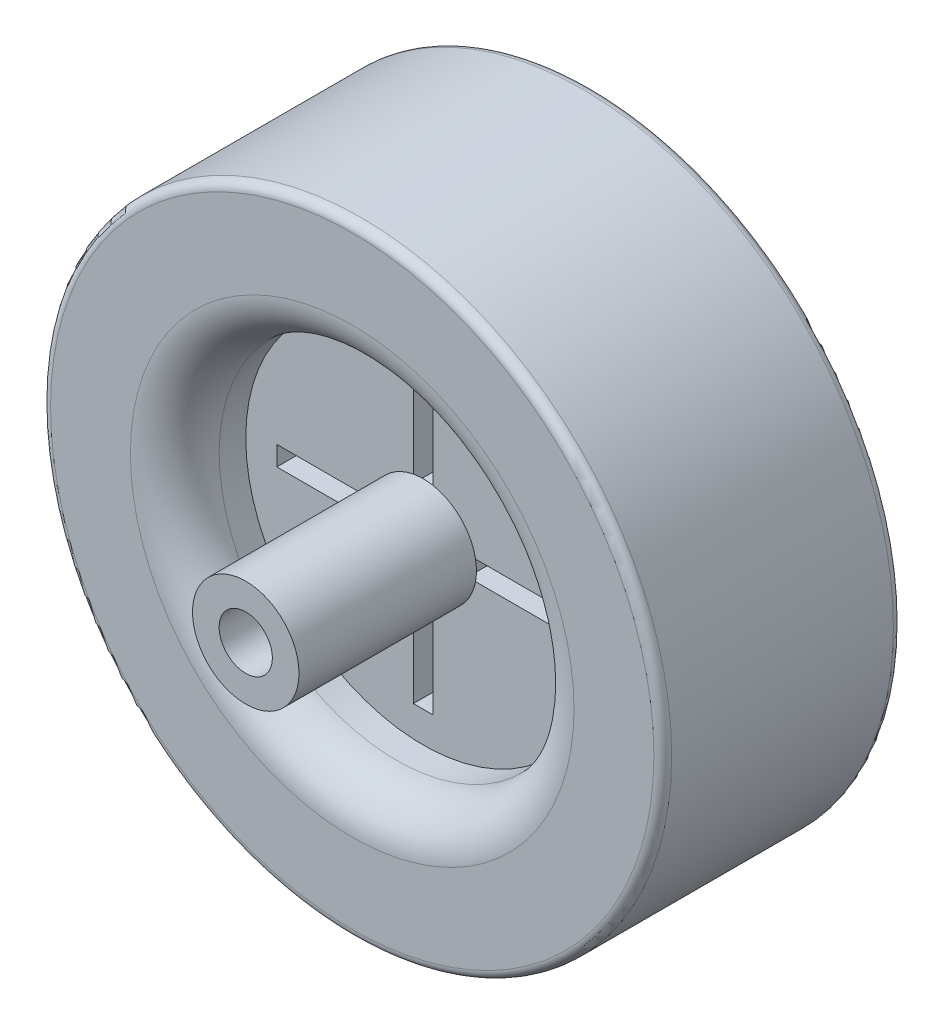
SolidWorks part; units mm, degrees
ref_plane "前视基准面" through (0, 0, 0) normal (0, 0, 1) x (1, 0, 0)
ref_plane "上视基准面" through (0, 0, 0) normal (0, 1, 0) x (1, 0, 0)
ref_plane "右视基准面" through (0, 0, 0) normal (1, 0, 0) x (0, 0, -1)
sketch "草图1" plane through (0, 0, 0) normal (0, 0, 1) x (1, 0, 0)
  circle A0 centre (0, 0) radius 35
extrude "凸台-拉伸1" add sketch "草图1" along normal blind 27
sketch "草图2" plane through (0, 0, 0) normal (0, 0, -1) x (-1, 0, 0)
  circle A0 centre (0, 0) radius 20
extrude "切除-拉伸1" cut sketch "草图2" against normal blind 8
sketch "草图3" plane through (0, 0, 27) normal (0, 0, 1) x (1, 0, 0)
  circle A0 centre (0, 0) radius 20
extrude "切除-拉伸2" cut sketch "草图3" against normal blind 8
fillet "圆角3" radius 5 1 edges at (-20, 0, 0)
fillet "圆角4" radius 5 1 edges at (20, 0, 27)
sketch "草图4" plane through (0, 0, 19) normal (0, 0, 1) x (1, 0, 0)
  circle A0 centre (0, 0) radius 6
extrude "凸台-拉伸2" add sketch "草图4" along normal blind 20
sketch "草图5" plane through (0, 0, 39) normal (0, 0, 1) x (1, 0, 0)
  circle A0 centre (0, 0) radius 3
extrude "切除-拉伸3" cut sketch "草图5" against normal blind 6
fillet "圆角5" radius 1 1 edges at (35, 0, 0)
fillet "圆角6" radius 1 1 edges at (35, 0, 27)
sketch "草图6" plane through (0, 0, 8) normal (0, 0, -1) x (-1, 0, 0)
  line L0 (16.5, 0) -> (-16.5, 0) construction
  line L1 (0, -16.5) -> (0, 16.5) construction
  line L2 (-11.6673, -11.6673) -> (11.6673, 11.6673) construction
  line L3 (11.6673, -11.6673) -> (-11.6673, 11.6673) construction
  line L4 (5, 1.1) -> (5, -1.1)
  line L9 (-1.1, -16.5) -> (1.1, -16.5)
  line L10 (-1.1, -16.5) -> (-1.1, -5)
  line L11 (-1.1, -5) -> (1.1, -5)
  line L12 (1.1, -16.5) -> (1.1, -5)
  line L13 (16.5, -1.1) -> (5, -1.1)
  line L14 (16.5, 1.1) -> (16.5, -1.1)
  line L15 (16.5, 1.1) -> (5, 1.1)
  line L16 (-1.1, 5) -> (1.1, 5)
  line L17 (1.1, 16.5) -> (1.1, 5)
  line L18 (-1.1, 16.5) -> (1.1, 16.5)
  line L19 (-1.1, 16.5) -> (-1.1, 5)
  line L20 (-5, -1.1) -> (-5, 1.1)
  line L21 (-16.5, 1.1) -> (-5, 1.1)
  line L22 (-16.5, -1.1) -> (-16.5, 1.1)
  line L23 (-16.5, -1.1) -> (-5, -1.1)
  point P7 (0, 0)
  point P11 (0, 0)
  point P21 (0, 0)
  point P27 (1.1, -10.75)
  point P33 (0, 0)
  dimension "D1" = 11.5
  dimension "D2" = 2.2
  dimension "D3" = 1.1
extrude "切除-拉伸5" cut sketch "草图6" against normal blind 11
sketch "草图7" plane through (0, 0, 8) normal (0, 0, -1) x (-1, 0, 0)
  circle A0 centre (0, 0) radius 2
extrude "凸台-拉伸3" add sketch "草图7" along normal blind 4
fillet "圆角8" radius 2 1 edges at (-2, 0, 4)
